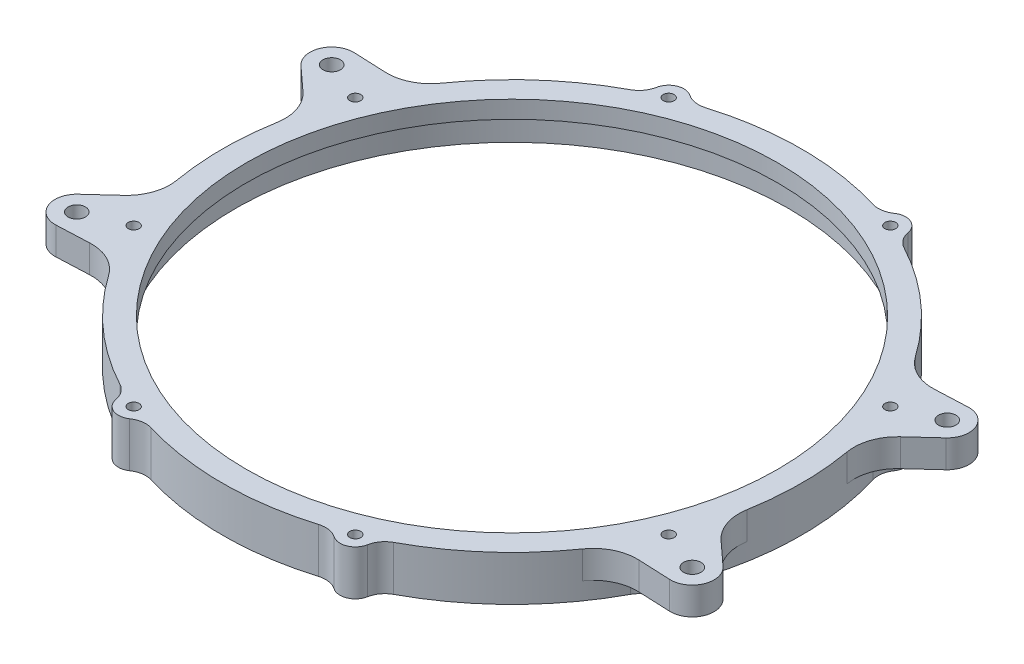
SolidWorks part; units mm, degrees
material "6061 合金"
ref_plane "前视基准面" through (0, 0, 0) normal (0, 0, 1) x (1, 0, 0)
ref_plane "上视基准面" through (0, 0, 0) normal (0, 1, 0) x (1, 0, 0)
ref_plane "右视基准面" through (0, 0, 0) normal (1, 0, 0) x (0, 0, -1)
other "Configuration Table"
sketch "草图1" plane through (0, 0, 0) normal (0, 1, 0) x (1, 0, 0)
  line L0 (0, -74.8) -> (0, 0) construction
  line L1 (0, 0) -> (25.4484, 61.438) construction
  line L2 (-28, -69.8) -> (28, -69.8) construction
  line L3 (28, -69.8) -> (18, -92.8) construction
  line L4 (18, -92.8) -> (-18, -92.8) construction
  line L5 (-18, -92.8) -> (-28, -69.8) construction
  line L6 (0, 0) -> (35.2391, -85.0747) construction
  circle A0 centre (0, 0) radius 50 construction
  circle A1 centre (0, 0) radius 66.5 construction
  circle A2 centre (0, -74.8) radius 6.8
  circle A3 centre (25.4484, 61.438) radius 1.2
  circle A4 centre (61.438, 25.4484) radius 1.2
  circle A5 centre (61.438, -25.4484) radius 1.2
  circle A6 centre (25.4484, -61.438) radius 1.2
  circle A7 centre (-25.4484, -61.438) radius 1.2
  circle A8 centre (-61.438, -25.4484) radius 1.2
  circle A9 centre (-61.438, 25.4484) radius 1.2
  circle A10 centre (-25.4484, 61.438) radius 1.2
  circle A16 centre (0, -74.8) radius 24.25 construction
  circle A17 centre (0, 0) radius 68 construction
  circle A18 centre (28, -69.8) radius 1.5
  circle A19 centre (28, -69.8) radius 3 construction
  circle A20 centre (-28, -69.8) radius 1.5
  circle A21 centre (-18, -92.8) radius 1.5
  circle A22 centre (18, -92.8) radius 1.5
  circle A23 centre (22.5, -65.755) radius 3 construction
  point P24 (0, 0)
  line B0 (-22.5, -65.755) -> (22.7731, -83.1337) construction
  line B1 (22.5, -65.755) -> (-22.7731, -83.1337) construction
  line B2 (-11.076, -59.0961) -> (11.076, -59.0961) construction
  circle B3 centre (22.7731, -83.1337) radius 1.6
  circle B4 centre (22.5, -65.755) radius 1.6
  circle B5 centre (-22.7731, -83.1337) radius 1.6
  circle B6 centre (-22.5, -65.755) radius 1.6
  circle B7 centre (0, -74.8) radius 20.5 construction
  circle B8 centre (0, -74.8) radius 17.6 construction
  circle B9 centre (0.0155, 17.5) radius 2.6
  circle B10 centre (0, 0) radius 11
  circle B11 centre (-15.1632, -8.7366) radius 2.6
  circle B12 centre (15.1477, -8.7634) radius 2.6
  circle B13 centre (0, 0) radius 22
  dimension "D1" = 100
  dimension "D3" = 133
  dimension "D4" = 13.6
  dimension "D5" = 2.4
  dimension "D8" = 3
  dimension "D9" = 6
  dimension "D10" = 5
  dimension "D14" = 6
  dimension "D2" = 74.8
  dimension "D7" = 157.5
  dimension "D11" = 36
  dimension "D12" = 18
  dimension "D13" = 56
  dimension "D6" = 8
sketch_block_instance "块-轮系转向电机定子固定-1"
sketch_block "块-轮系转向电机定子固定" parameters "D1"=41, "D2"=35.2
sketch_block_instance "块-R1-滑环-2022-1"
sketch_block "块-R1-滑环-2022"
sketch "草图3" plane through (0, 0, 0) normal (0, 1, 0) x (1, 0, 0)
  line L0 (20.5252, -90.754) -> (28.226, -73.0421)
  line L1 (28, -69.8) -> (18, -92.8) construction
  line L2 (17.774, -89.5579) -> (25.4748, -71.846)
  line L3 (0, 0) -> (35.2391, -85.0747) construction
  line L4 (30.5252, -67.754) -> (35.5481, -56.2012)
  line L5 (27.2524, -66.6371) -> (26.7878, -64.6716)
  line L6 (0, -66.5) -> (15.3175, -90.9652)
  line L7 (17.5212, -89.5855) -> (3.0245, -66.4312)
  line L8 (18, -92.8) -> (1.5229, -66.4826) construction
  line L9 (0, -74.8) -> (0, 0) construction
  line L10 (0, -74.8) -> (0, 0) construction
  line L11 (0, -66.5) -> (-15.3175, -90.9652)
  line L12 (-17.5212, -89.5855) -> (-3.0245, -66.4312)
  line L13 (-17.774, -89.5579) -> (-25.4748, -71.846)
  line L14 (-20.5252, -90.754) -> (-28.226, -73.0421)
  line L15 (-27.2524, -66.6371) -> (-26.7878, -64.6716)
  line L16 (-30.5252, -67.754) -> (-35.5481, -56.2012)
  line L17 (-15.6078, -95) -> (15.6078, -95)
  line L18 (18, -92.8) -> (-18, -92.8) construction
  line L19 (-14.85, -92) -> (14.85, -92)
  arc A0 (17.774, -89.5579) -> (17.5212, -89.5855) centre (18, -92.8) ccw
  circle A1 centre (25.4484, -61.438) radius 1.2
  circle A2 centre (25.4484, -61.438) radius 1.2
  circle A3 centre (61.438, -25.4484) radius 1.2
  circle A4 centre (61.438, -25.4484) radius 1.2
  circle A5 centre (61.438, 25.4484) radius 1.2
  circle A6 centre (61.438, 25.4484) radius 1.2
  circle A7 centre (25.4484, 61.438) radius 1.2
  circle A8 centre (25.4484, 61.438) radius 1.2
  arc A9 (15.6078, -95) -> (20.5252, -90.754) centre (18, -92.8) ccw
  circle A11 centre (28, -69.8) radius 1.5
  circle A12 centre (28, -69.8) radius 1.5
  circle A13 centre (-25.4484, 61.438) radius 1.2
  circle A14 centre (-25.4484, 61.438) radius 1.2
  circle A15 centre (-61.438, 25.4484) radius 1.2
  circle A16 centre (-61.438, 25.4484) radius 1.2
  circle A17 centre (-61.438, -25.4484) radius 1.2
  circle A18 centre (-61.438, -25.4484) radius 1.2
  circle A19 centre (-25.4484, -61.438) radius 1.2
  circle A20 centre (-25.4484, -61.438) radius 1.2
  circle A21 centre (18, -92.8) radius 1.5
  circle A22 centre (18, -92.8) radius 1.5
  circle A23 centre (-18, -92.8) radius 1.5
  circle A24 centre (-18, -92.8) radius 1.5
  circle A25 centre (-28, -69.8) radius 1.5
  circle A26 centre (-28, -69.8) radius 1.5
  arc A27 (27.2524, -66.6371) -> (25.4748, -71.846) centre (28, -69.8) ccw
  arc A28 (-15.3175, -90.9652) -> (-14.85, -92) centre (-18, -92.8) cw
  arc A29 (-27.2524, -66.6371) -> (-25.4748, -71.846) centre (-28, -69.8) cw
  arc A30 (-28.226, -73.0421) -> (-30.5252, -67.754) centre (-28, -69.8) cw
  arc A31 (0, -66.5) -> (1.5229, -66.4826) centre (0, 0) ccw construction
  arc A32 (3.0245, -66.4312) -> (22.1807, -62.6918) centre (0, 0) ccw
  arc A33 (-17.774, -89.5579) -> (-17.5212, -89.5855) centre (-18, -92.8) cw
  arc A34 (-15.6078, -95) -> (-20.5252, -90.754) centre (-18, -92.8) cw
  circle A44 centre (0, 0) radius 66.5 construction
  arc A45 (22.1807, 62.6918) -> (-22.1807, 62.6918) centre (0, 0) ccw
  arc A46 (28.6457, 60.014) -> (22.1807, 62.6918) centre (25.4484, 61.438) ccw
  arc A47 (62.6918, 22.1807) -> (60.014, 28.6457) centre (61.438, 25.4484) ccw
  arc A48 (60.014, -28.6457) -> (62.6918, -22.1807) centre (61.438, -25.4484) ccw
  arc A49 (22.1807, -62.6918) -> (26.7878, -64.6716) centre (25.4484, -61.438) ccw
  arc A50 (-26.7878, -64.6716) -> (-22.1807, -62.6918) centre (-25.4484, -61.438) ccw
  arc A51 (-62.6918, -22.1807) -> (-60.014, -28.6457) centre (-61.438, -25.4484) ccw
  arc A52 (-60.014, 28.6457) -> (-62.6918, 22.1807) centre (-61.438, 25.4484) ccw
  arc A53 (-22.1807, 62.6918) -> (-28.6457, 60.014) centre (-25.4484, 61.438) ccw
  circle A54 centre (0, 0) radius 61
  arc A55 (62.6918, -22.1807) -> (62.6918, 22.1807) centre (0, 0) ccw
  arc A56 (60.014, 28.6457) -> (28.6457, 60.014) centre (0, 0) ccw
  arc A57 (35.5481, -56.2012) -> (60.014, -28.6457) centre (0, 0) ccw
  arc A58 (-22.1807, -62.6918) -> (-3.0245, -66.4312) centre (0, 0) ccw
  arc A59 (-60.014, -28.6457) -> (-35.5481, -56.2012) centre (0, 0) ccw
  arc A60 (-28.6457, 60.014) -> (-60.014, 28.6457) centre (0, 0) ccw
  arc A61 (-62.6918, 22.1807) -> (-62.6918, -22.1807) centre (0, 0) ccw
  arc A63 (15.3175, -90.9652) -> (14.85, -92) centre (18, -92.8) ccw
  arc A64 (28.226, -73.0421) -> (30.5252, -67.754) centre (28, -69.8) ccw
  point P71 (0, 0)
  dimension "D14" = 7
  dimension "D16" = 122
  dimension "D18" = 6.5
  dimension "D19" = 2.6
  dimension "D5" = 1.5
  dimension "D17" = 1.5
  dimension "D20" = 2.2
  dimension "D21" = 3
  dimension "D1" = 0
  dimension "D2" = 0
  dimension "D3" = 0
  dimension "D4" = 0
  dimension "D6" = 0
  dimension "D7" = 0
  dimension "D8" = 0
  dimension "D9" = 0
  dimension "D10" = 0
  dimension "D11" = 0
  dimension "D12" = 0
  dimension "D13" = 0
  dimension "D15" = 8
extrude "凸台-拉伸1" add sketch "草图3" along normal blind 10.35
sketch "草图4" plane through (0, 0, 0) normal (0, -1, 0) x (1, 0, 0)
  circle A0 centre (0, 0) radius 63.5
  dimension "D1" = 127
extrude "切除-拉伸1" cut sketch "草图4" against normal blind 6.35
sketch "草图5" plane through (0, 0, 0) normal (0, -1, 0) x (1, 0, 0)
  arc A0 (22.1807, 62.6918) -> (-22.1807, 62.6918) centre (0, 0) ccw
  arc A1 (-35.5481, 56.2012) -> (-60.014, 28.6457) centre (0, 0) ccw construction
  arc A2 (-22.1807, 62.6918) -> (-28.6457, 60.014) centre (-25.4484, 61.438) ccw
  arc A3 (28.6457, 60.014) -> (22.1807, 62.6918) centre (25.4484, 61.438) ccw
  arc A4 (62.6918, 22.1807) -> (60.014, 28.6457) centre (61.438, 25.4484) ccw
  arc A5 (60.014, -28.6457) -> (62.6918, -22.1807) centre (61.438, -25.4484) ccw
  arc A6 (22.1807, -62.6918) -> (28.6457, -60.014) centre (25.4484, -61.438) ccw
  arc A7 (-28.6457, -60.014) -> (-22.1807, -62.6918) centre (-25.4484, -61.438) ccw
  arc A8 (-62.6918, -22.1807) -> (-60.014, -28.6457) centre (-61.438, -25.4484) ccw
  arc A9 (-60.014, 28.6457) -> (-62.6918, 22.1807) centre (-61.438, 25.4484) ccw
  arc A10 (-28.6457, 60.014) -> (-60.014, 28.6457) centre (0, 0) ccw
  arc A11 (60.014, 28.6457) -> (28.6457, 60.014) centre (0, 0) ccw
  arc A12 (62.6918, -22.1807) -> (62.6918, 22.1807) centre (0, 0) ccw
  arc A13 (28.6457, -60.014) -> (60.014, -28.6457) centre (0, 0) ccw
  arc A14 (-22.1807, -62.6918) -> (22.1807, -62.6918) centre (0, 0) ccw
  arc A15 (-60.014, -28.6457) -> (-28.6457, -60.014) centre (0, 0) ccw
  arc A16 (-62.6918, 22.1807) -> (-62.6918, -22.1807) centre (0, 0) ccw
  point P25 (0, 0)
  dimension "D1" = 7
  dimension "D2" = 8
extrude "切除-拉伸2" cut sketch "草图5" against normal blind 13.5 flip side to cut
fillet "圆角1" radius 5 8 edges at (-22.1807, 5.175, -62.6918) (-28.6457, 5.175, -60.014) (22.1807, 5.175, -62.6918) (28.6457, 5.175, -60.014) (28.6457, 5.175, 60.014) (22.1807, 5.175, 62.6918) (-22.1807, 5.175, 62.6918) (-28.6457, 5.175, 60.014)
sketch "草图6" plane through (0, 10.35, 0) normal (0, 1, 0) x (1, 0, 0)
  point P0 (-25.4484, 61.438)
  point P3 (25.4484, 61.438)
  point P6 (61.438, 25.4484)
  point P9 (61.438, -25.4484)
  point P12 (25.4484, -61.438)
  point P15 (-25.4484, -61.438)
  point P18 (-61.438, -25.4484)
  point P21 (-61.438, 25.4484)
  point P25 (25.4484, 61.438)
  point P27 (-25.4484, 61.438)
  point P30 (-61.438, 25.4484)
  point P32 (-61.438, -25.4484)
  point P34 (-25.4484, -61.438)
  point P36 (25.4484, -61.438)
  point P38 (61.438, -25.4484)
  point P40 (61.438, 25.4484)
hole_wizard "M3 螺纹孔1" positions "草图6" profile "草图7" tap size "M3" standard "GB" end condition through all
cosmetic thread "孔螺蚊线1" parameters "D2"=3
cosmetic thread "孔螺蚊线2" parameters "D2"=3
cosmetic thread "孔螺蚊线3" parameters "D2"=3
cosmetic thread "孔螺蚊线4" parameters "D2"=3
cosmetic thread "孔螺蚊线5" parameters "D2"=3
cosmetic thread "孔螺蚊线6" parameters "D2"=3
cosmetic thread "孔螺蚊线7" parameters "D2"=3
cosmetic thread "孔螺蚊线8" parameters "D2"=3
sketch "草图7" plane through (-25.4484, 10.35, -61.438) normal (1, 0, 0) x (0, 0, 1)
  line L0 (0, 0) -> (0, 10.35)
  line L1 (0, 10.35) -> (1.25, 10.35)
  line L2 (1.25, 10.35) -> (1.25, 0)
  line L5 (1.25, 0) -> (0, 0)
  line L11 (0, -6.35) -> (0, 107.95) construction
  dimension "通孔螺纹孔钻头直径" = 2.5
  dimension "通孔螺纹孔钻头深度" = 10.35
sketch "草图8" plane through (0, 0, 0) normal (0, 1, 0) x (1, 0, 0)
  line L0 (70.6768, 29.2753) -> (-61.438, -25.4484) construction
  line L1 (70.4587, 34.2705) -> (57.3301, 33.6973)
  line L2 (74.0547, 25.5889) -> (64.3661, 16.7109)
  arc A0 (62.6918, 22.1807) -> (60.014, 28.6457) centre (61.438, 25.4484) ccw construction
  circle A2 centre (70.6768, 29.2753) radius 2
  arc A3 (74.0547, 25.5889) -> (70.4587, 34.2705) centre (70.6768, 29.2753) ccw
  circle A4 centre (61.438, 25.4484) radius 1.25 construction
  arc A5 (60.014, 28.6457) -> (31.4389, 58.599) centre (0, 0) ccw construction
  arc A6 (62.6918, 22.1807) -> (60.014, 28.6457) centre (61.438, 25.4484) ccw
  arc A7 (62.6918, -22.1807) -> (62.6918, 22.1807) centre (0, 0) ccw construction
  arc A8 (60.014, 28.6457) -> (57.3301, 33.6973) centre (0, 0) ccw
  arc A9 (64.3661, 16.7109) -> (62.6918, 22.1807) centre (0, 0) ccw
  dimension "D1" = 4
  dimension "D2" = 10
  dimension "D3" = 10
  dimension "D4" = 20
extrude "凸台-拉伸2" add sketch "草图8" along normal up to surface (10.35 mm away) up to face at (25.4484, 10.35, -60.188)
sketch "草图9" plane through (0, 0, 0) normal (0, -1, 0) x (1, 0, 0)
  line L0 (70.4587, -34.2705) -> (57.3301, -33.6973) construction
  line L1 (64.3661, -16.7109) -> (74.0547, -25.5889) construction
  line L2 (70.4587, -34.2705) -> (57.3301, -33.6973)
  line L3 (64.3661, -16.7109) -> (74.0547, -25.5889)
  arc A0 (60.014, -28.6457) -> (62.6918, -22.1807) centre (61.438, -25.4484) ccw
  arc A1 (57.3301, -33.6973) -> (60.014, -28.6457) centre (0, 0) ccw
  arc A2 (64.3661, -16.7109) -> (62.6918, 22.1807) centre (0, 0) ccw construction
  arc A3 (70.4587, -34.2705) -> (74.0547, -25.5889) centre (70.6768, -29.2753) ccw construction
  arc A4 (70.4587, -34.2705) -> (74.0547, -25.5889) centre (70.6768, -29.2753) ccw
  arc A5 (62.6918, -22.1807) -> (64.3661, -16.7109) centre (0, 0) ccw
  dimension "D1" = 7
extrude "切除-拉伸3" cut sketch "草图9" against normal blind 4
mirror "镜向1" about plane through (0, 0, 0) normal (0, 0, 1) of "凸台-拉伸2"
mirror "镜向2" about plane through (0, 0, 0) normal (0, 0, 1) of "切除-拉伸3"
mirror "镜向3" about plane through (0, 0, 0) normal (1, 0, 0) of "镜向2", "切除-拉伸3", "凸台-拉伸2", "镜向1"
fillet "圆角5" radius 5 8 edges at (-60.014, 2, 28.6457) (-62.6918, 2, 22.1807) (-62.6918, 2, -22.1807) (-60.014, 2, -28.6457) (60.014, 2, -28.6457) (62.6918, 2, -22.1807) (62.6918, 2, 22.1807) (60.014, 2, 28.6457)
fillet "圆角6" radius 10 8 edges at (-64.3661, 7.175, -16.7109) (-57.3301, 7.175, -33.6973) (57.3301, 7.175, -33.6973) (64.3661, 7.175, -16.7109) (64.3661, 7.175, 16.7109) (57.3301, 7.175, 33.6973) (-64.3661, 7.175, 16.7109) (-57.3301, 7.175, 33.6973)
